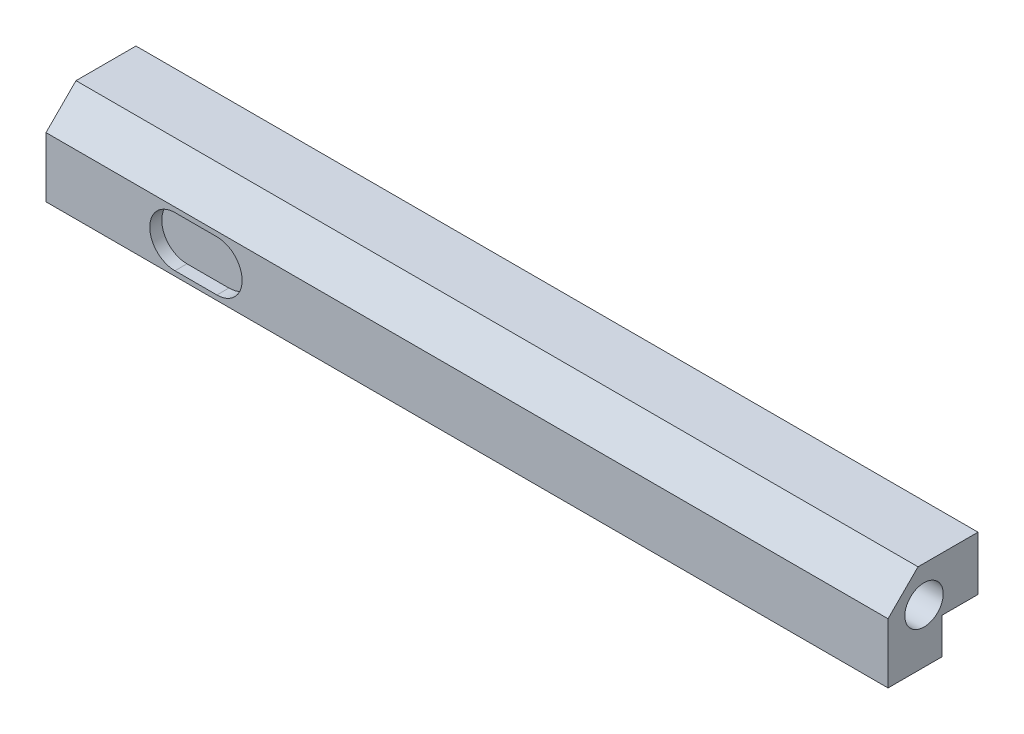
SolidWorks part; units mm, degrees
ref_plane "Plan de face" through (0, 0, 0) normal (0, 0, 1) x (1, 0, 0)
ref_plane "Plan de dessus" through (0, 0, 0) normal (0, 1, 0) x (1, 0, 0)
ref_plane "Plan de droite" through (0, 0, 0) normal (1, 0, 0) x (0, 0, -1)
sketch "Esquisse3" plane through (0, 0, 0) normal (1, 0, 0) x (0, 0, -1)
  line L0 (-4.5, -10.5) -> (-4.5, 4.5)
  line L1 (-4.5, 4.5) -> (10.5, 4.5)
  line L2 (10.5, 4.5) -> (10.5, -4.5)
  line L3 (10.5, -4.5) -> (4.5, -4.5)
  line L4 (4.5, -4.5) -> (4.5, -10.5)
  line L5 (4.5, -10.5) -> (-4.5, -10.5)
  line L6 (-4.5, 4.5) -> (4.5, -4.5) construction
  circle A1 centre (1.5, -1.5) radius 2.35
  point P8 (0, 0)
  dimension "D4" = 4.7
  dimension "D5" = 6
  dimension "D6" = 6
  dimension "D1" = 9
  dimension "D2" = 9
  dimension "D3" = 15
extrude "Boss.-Extru.2" add sketch "Esquisse3" along normal mid plane 140.4
chamfer "Chanfrein1" distance 5 angle 45 1 edges at (0, 4.5, 4.5)
sketch "Esquisse6" plane through (-70.2, 0, 0) normal (-1, 0, 0) x (0, 0, 1)
  circle A0 centre (-1.5, -1.5) radius 2.35 construction
  circle A1 centre (-1.5, -1.5) radius 2.35
  circle A2 centre (-1.5, -1.5) radius 3.2
  dimension "D1" = 6.4
extrude "Enlèv. mat.-Extru.1" cut sketch "Esquisse6" against normal blind 7
sketch "Esquisse7" plane through (70.2, 0, 0) normal (1, 0, 0) x (0, 0, -1)
  circle A0 centre (1.5, -1.5) radius 2.35 construction
  circle A1 centre (1.5, -1.5) radius 2.35
  circle A2 centre (1.5, -1.5) radius 3.2
  dimension "D1" = 6.4
extrude "Enlèv. mat.-Extru.2" cut sketch "Esquisse7" against normal blind 7
sketch "Esquisse9" plane through (0, 0, 4.5) normal (0, 0, 1) x (1, 0, 0)
  line L0 (-70.2, -5.5) -> (70.2, -5.5) construction
  line L1 (-70.2, -0.5) -> (-70.2, -10.5) construction
  line L2 (70.2, -0.5) -> (70.2, -10.5) construction
  line L3 (-48.7, -5.5) -> (-41.7, -5.5) construction
  line L4 (-48.7, -1.3) -> (-41.7, -1.3)
  line L5 (-48.7, -9.7) -> (-41.7, -9.7)
  arc A0 (-48.7, -1.3) -> (-48.7, -9.7) centre (-48.7, -5.5) ccw
  arc A1 (-41.7, -9.7) -> (-41.7, -1.3) centre (-41.7, -5.5) ccw
  point P8 (-45.2, -5.5)
  point P13 (-52.9, -5.5)
  point P14 (-37.5, -5.5)
  dimension "D1" = 15.4
  dimension "D2" = 8.4
  dimension "D3" = 25
extrude "Enlèv. mat.-Extru.4" cut sketch "Esquisse9" against normal blind 2
